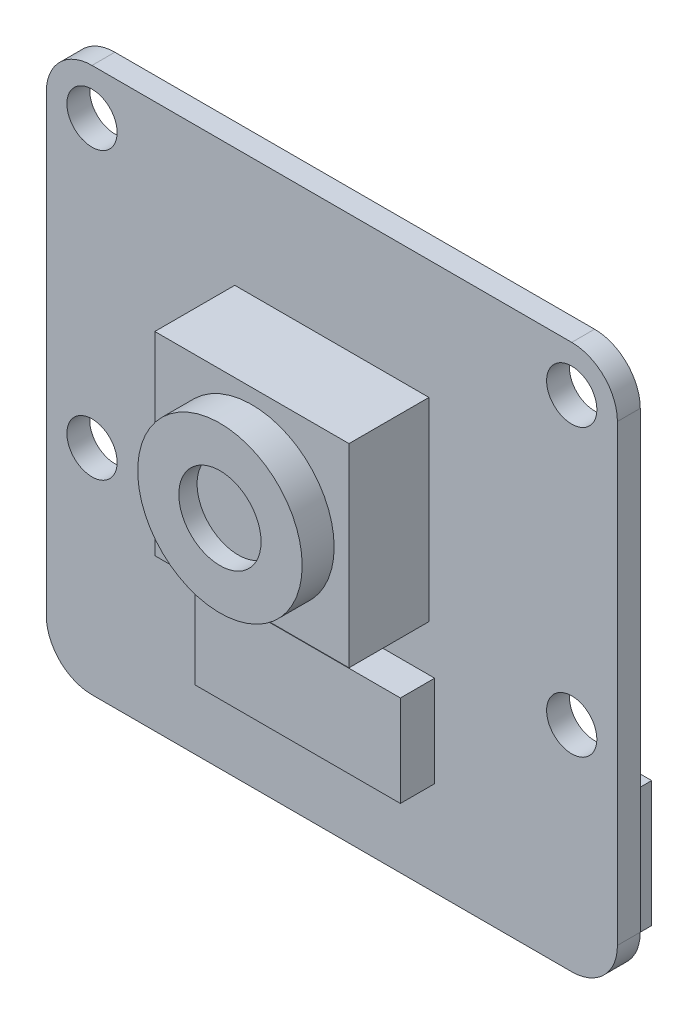
SolidWorks part; units mm, degrees
ref_plane "Front Plane" through (0, 0, 0) normal (0, 0, 1) x (1, 0, 0)
ref_plane "Top Plane" through (0, 0, 0) normal (0, 1, 0) x (1, 0, 0)
ref_plane "Right Plane" through (0, 0, 0) normal (1, 0, 0) x (0, 0, -1)
sketch "Sketch1" plane through (0, 0, 0) normal (0, 0, 1) x (1, 0, 0)
  line L1 (-12.5, -11.931) -> (12.5, -11.931)
  line L2 (-12.5, -11.931) -> (-12.5, 11.931)
  line L3 (-12.5, 11.931) -> (12.5, 11.931)
  line L4 (12.5, -11.931) -> (12.5, 11.931)
extrude "PCB_Board" add sketch "Sketch1" along normal blind 1
fillet "PCB_Corner_Fillets" radius 2 4 edges at (-12.5, 11.931, 0.5) (12.5, 11.931, 0.5) (12.5, -11.931, 0.5) (-12.5, -11.931, 0.5)
sketch "Sketch2" plane through (0, 0, 1) normal (0, 0, 1) x (1, 0, 0)
  circle A0 centre (10.5, 9.931) radius 1.1
  circle A1 centre (-10.5, 9.931) radius 1.1
  circle A2 centre (10.5, -2.569) radius 1.1
  circle A3 centre (-10.5, -2.569) radius 1.1
extrude "Mounting_Holes" cut sketch "Sketch2" against normal through all
sketch "Sketch3" plane through (0, 0, 1) normal (0, 0, 1) x (1, 0, 0)
  line L1 (-4.25, -1.781) -> (4.25, -1.781)
  line L2 (-4.25, -1.781) -> (-4.25, 6.719)
  line L3 (-4.25, 6.719) -> (4.25, 6.719)
  line L4 (4.25, -1.781) -> (4.25, 6.719)
extrude "Sensor_Housing" add sketch "Sketch3" along normal blind 3.5
sketch "Sketch4" plane through (0, 0, 4.5) normal (0, 0, 1) x (1, 0, 0)
  circle A0 centre (0, 2.469) radius 3.6
extrude "Lens_Barrel" add sketch "Sketch4" along normal blind 1.4
sketch "Sketch5" plane through (0, 0, 5.9) normal (0, 0, 1) x (1, 0, 0)
  circle A0 centre (0, 2.469) radius 1.8
extrude "Lens_Aperture" cut sketch "Sketch5" against normal blind 0.8
sketch "Sketch6" plane through (0, 0, 0) normal (0, 0, -1) x (-1, 0, 0)
  line L1 (-10.5, -11.931) -> (10.5, -11.931)
  line L2 (-10.5, -11.931) -> (-10.5, -6.431)
  line L3 (-10.5, -6.431) -> (10.5, -6.431)
  line L4 (10.5, -11.931) -> (10.5, -6.431)
extrude "CSI_Connector" add sketch "Sketch6" along normal blind 2.5
sketch "Sketch7" plane through (0, 0, 1) normal (0, 0, 1) x (1, 0, 0)
  line L1 (-4.5, -7.8) -> (4.5, -7.8)
  line L2 (-4.5, -7.8) -> (-4.5, -3.8)
  line L3 (-4.5, -3.8) -> (4.5, -3.8)
  line L4 (4.5, -7.8) -> (4.5, -3.8)
extrude "Flex_Connector" add sketch "Sketch7" along normal blind 1.5
